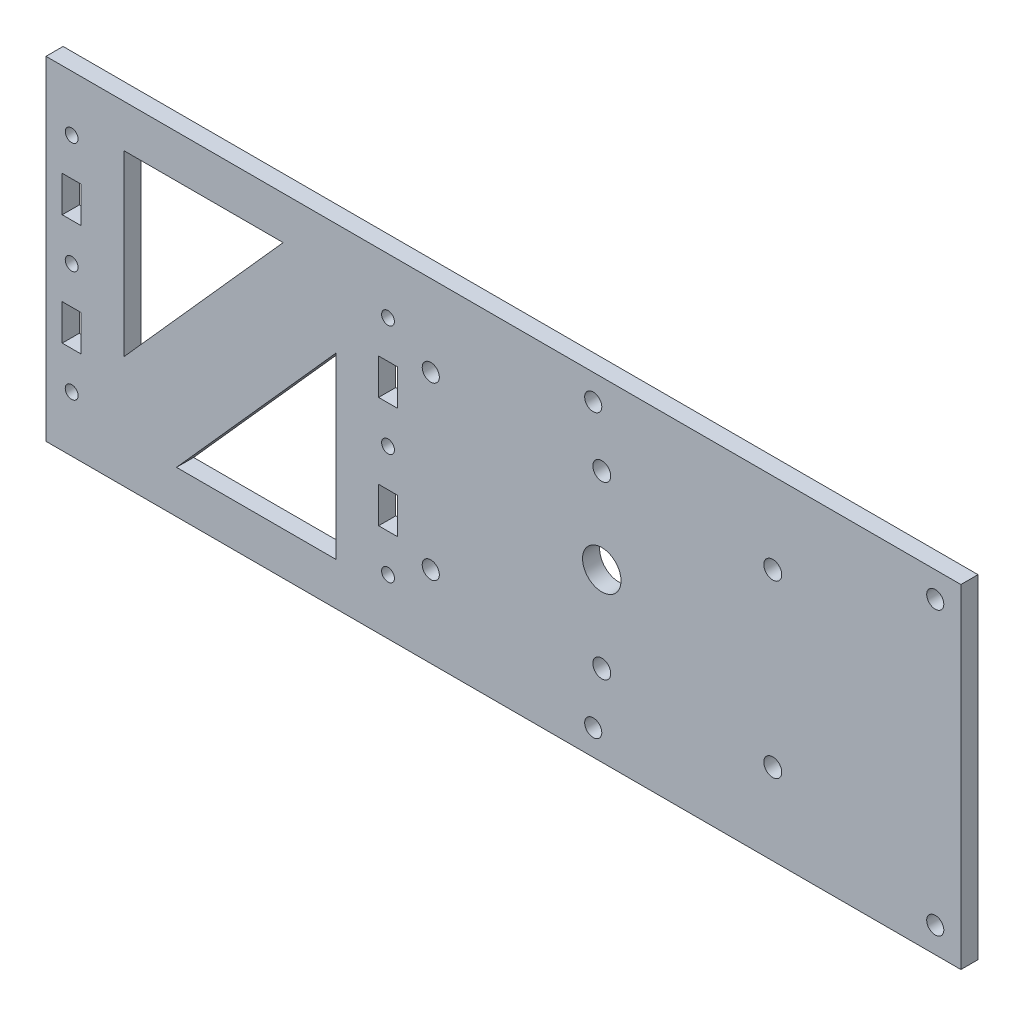
SolidWorks part; units mm, degrees
ref_plane "前视基准面" through (0, 0, 0) normal (0, 0, 1) x (1, 0, 0)
ref_plane "上视基准面" through (0, 0, 0) normal (0, 1, 0) x (1, 0, 0)
ref_plane "右视基准面" through (0, 0, 0) normal (1, 0, 0) x (0, 0, -1)
sketch "草图1" plane through (0, 0, 0) normal (0, 0, 1) x (1, 0, 0)
  line L0 (0, 0) -> (0, 13) construction
  line L1 (0, 13) -> (-8.8556, 13) construction
  line L2 (-2.2, 17.2) -> (2.2, 17.2)
  line L3 (-2.2, 17.2) -> (-2.2, 8.8)
  line L4 (-2.2, 8.8) -> (2.2, 8.8)
  line L5 (2.2, 17.2) -> (2.2, 8.8)
  line L6 (-2.2, 17.2) -> (2.2, 8.8) construction
  line L7 (-2.2, 8.8) -> (2.2, 17.2) construction
  line L8 (0, 26) -> (7.7263, 26) construction
  line L13 (0, 0) -> (-13.815, 0) construction
  line L14 (-2.2, -8.8) -> (2.2, -17.2) construction
  line L15 (-2.2, -17.2) -> (2.2, -8.8) construction
  line L16 (0, -13) -> (-8.8556, -13) construction
  line L17 (2.2, -17.2) -> (2.2, -8.8)
  line L18 (-2.2, -8.8) -> (2.2, -8.8)
  line L19 (-2.2, -17.2) -> (-2.2, -8.8)
  line L20 (-2.2, -17.2) -> (2.2, -17.2)
  line L21 (0, 0) -> (50, 0) construction
  line L22 (-6, 39) -> (134, 39)
  line L23 (-6, 39) -> (-6, -39) construction
  line L24 (-6, -39) -> (134, -39)
  line L25 (134, 39) -> (134, -39)
  line L26 (50, 0) -> (70, 0) construction
  line L27 (50, 20) -> (50, -20) construction
  line L28 (50, -20) -> (90, -20) construction
  line L29 (50, 20) -> (90, 20) construction
  line L30 (0, 0) -> (-74, 0) construction
  line L31 (-37, 0) -> (-37, 6.0392) construction
  line L32 (-71.8, 8.8) -> (-76.2, 8.8)
  line L33 (-71.8, 17.2) -> (-76.2, 17.2)
  line L34 (-76.2, 17.2) -> (-76.2, 8.8)
  line L35 (-71.8, 17.2) -> (-71.8, 8.8)
  line L36 (-71.8, -8.8) -> (-76.2, -8.8)
  line L37 (-71.8, -17.2) -> (-76.2, -17.2)
  line L38 (-71.8, -17.2) -> (-71.8, -8.8)
  line L39 (-76.2, -17.2) -> (-76.2, -8.8)
  line L40 (-6, -39) -> (-80, -39)
  line L41 (-80, -39) -> (-80, 39)
  line L42 (-80, 39) -> (-6, 39)
  circle A0 centre (0, 0) radius 1.5
  circle A1 centre (0, 26) radius 1.5
  circle A2 centre (0, -26) radius 1.5
  circle A3 centre (50, 0) radius 4.5
  circle A4 centre (50, 20) radius 2.0968
  circle A21 centre (50, -20) radius 2.0968
  circle A22 centre (90, -20) radius 2.0968
  circle A23 centre (90, 20) radius 2.0968
  circle A24 centre (10, -20) radius 2
  circle A26 centre (10, 20) radius 2
  circle A27 centre (-74, 0) radius 1.5
  circle A28 centre (-74, 26) radius 1.5
  circle A29 centre (-74, -26) radius 1.5
  point P25 (-6, 0)
  dimension "D1" = 3
  dimension "D8" = 9
  dimension "D10" = 20
  dimension "D13" = 40
  dimension "D11" = 40
  dimension "D14" = 40
  dimension "D2" = 13
  dimension "D3" = 4.4
  dimension "D4" = 8.4
  dimension "D5" = 78
  dimension "D6" = 140
  dimension "D7" = 6
  dimension "D9" = 50
  dimension "D12" = 20
extrude "凸台-拉伸1" add sketch "草图1" along normal blind 4
sketch "草图2" plane through (0, 0, 0) normal (0, 0, -1) x (-1, 0, 0)
  line L0 (80, -39) -> (-134, -39) construction
  line L1 (-134, -39) -> (-134, 39) construction
  line L2 (2.2, 39) -> (2.2, -39) construction
  line L3 (-134, 39) -> (80, 39) construction
  line L4 (71.8, -39) -> (2.2, 39) construction
  line L5 (71.8, 39) -> (71.8, -39) construction
  line L6 (2.2, 39) -> (71.8, 39) construction
  line L7 (61.8, -12.7733) -> (24.5254, 29)
  line L8 (24.5254, 29) -> (61.8, 29)
  line L9 (61.8, 29) -> (61.8, -12.7733)
  line L10 (2.2, -39) -> (71.8, -39) construction
  line L11 (12.2, -29) -> (49.4746, -29)
  line L12 (49.4746, -29) -> (12.2, 12.7733)
  line L13 (12.2, 12.7733) -> (12.2, -29)
  circle A0 centre (-128, -33) radius 2
  circle A1 centre (-48, -33) radius 2
  circle A2 centre (-48, 33) radius 2
  circle A3 centre (-128, 33) radius 2
  dimension "D1" = 6
  dimension "D2" = 6
  dimension "D5" = 10
  dimension "D6" = 10
  dimension "D3" = 2
  dimension "D4" = 2
extrude "切除-拉伸1" cut sketch "草图2" against normal blind 10
